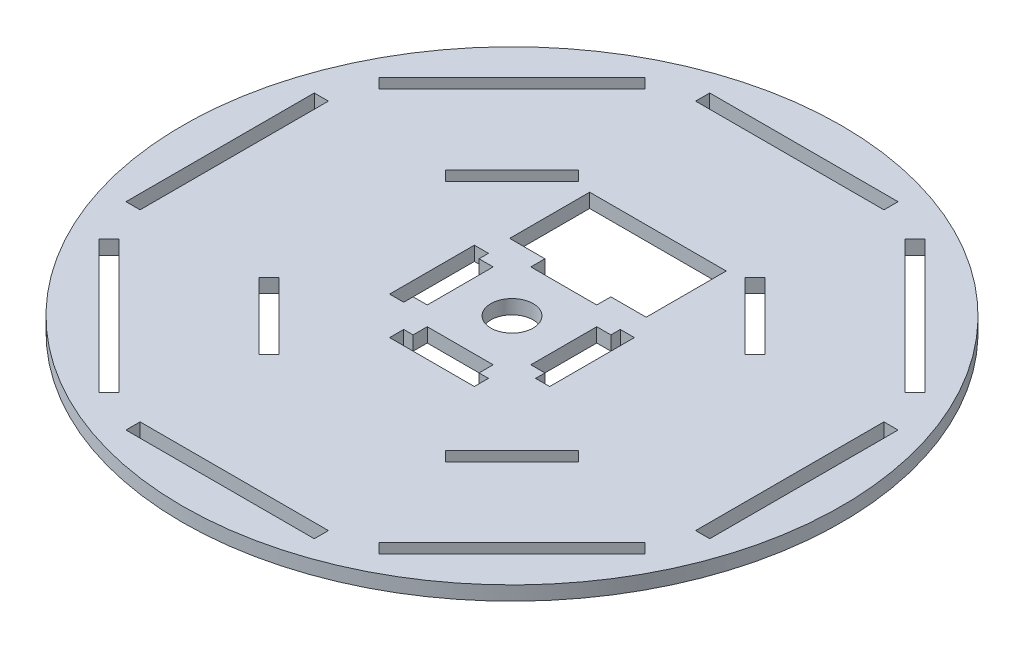
SolidWorks part; units mm, degrees
ref_plane "Alzado" through (0, 0, 0) normal (0, 0, 1) x (1, 0, 0)
ref_plane "Planta" through (0, 0, 0) normal (0, 1, 0) x (1, 0, 0)
ref_plane "Vista lateral" through (0, 0, 0) normal (1, 0, 0) x (0, 0, -1)
sketch "Croquis1" plane through (0, 0, 0) normal (0, 1, 0) x (1, 0, 0)
  line L0 (0, 11) -> (7, 11)
  line L1 (7, 11) -> (7, 14)
  line L2 (24.7487, 24.7487) -> (31.8198, 17.6777)
  line L3 (-7, 14) -> (-7, 11)
  line L4 (-7, 11) -> (0, 11)
  line L5 (11, 0) -> (11, 7)
  line L6 (11, 7) -> (14, 7)
  line L8 (14, -7) -> (11, -7)
  line L9 (11, -7) -> (11, 0)
  line L10 (0, 0) -> (-24.7487, 24.7487) construction
  line L11 (-24.7487, 24.7487) -> (-17.6777, 31.8198)
  line L12 (-17.6777, 31.8198) -> (-19.799, 33.9411)
  line L13 (-14, -7) -> (-11, -7)
  line L14 (-11, -7) -> (-11, 0)
  line L15 (-11, 0) -> (-11, 7)
  line L16 (-11, 7) -> (-14, 7)
  line L17 (-7, -14) -> (-9, -14)
  line L18 (7, -11) -> (7, -14)
  line L19 (0, -11) -> (7, -11)
  line L20 (14, -7) -> (14, -9)
  line L21 (-7, -14) -> (-7, -11)
  line L22 (-7, -11) -> (0, -11)
  line L23 (-19.799, 33.9411) -> (-33.9411, 19.799)
  line L24 (-24.7487, 24.7487) -> (-31.8198, 17.6777)
  line L25 (-31.8198, 17.6777) -> (-33.9411, 19.799)
  line L26 (7, 14) -> (14.5, 14)
  line L27 (14.5, 14) -> (14.5, 31)
  line L28 (14.5, 31) -> (-14.5, 31)
  line L29 (-14.5, 31) -> (-14.5, 14)
  line L30 (-14.5, 14) -> (-7, 14)
  line L31 (31.8198, 17.6777) -> (33.9411, 19.799)
  line L32 (33.9411, 19.799) -> (19.799, 33.9411)
  line L33 (17.6777, 31.8198) -> (19.799, 33.9411)
  line L34 (24.7487, 24.7487) -> (17.6777, 31.8198)
  line L35 (24.7487, -24.7487) -> (17.6777, -31.8198)
  line L36 (17.6777, -31.8198) -> (19.799, -33.9411)
  line L37 (19.799, -33.9411) -> (33.9411, -19.799)
  line L38 (31.8198, -17.6777) -> (33.9411, -19.799)
  line L39 (24.7487, -24.7487) -> (31.8198, -17.6777)
  line L40 (-24.7487, -24.7487) -> (-31.8198, -17.6777)
  line L41 (0, 0) -> (0, 62) construction
  line L42 (0, 62) -> (20, 62)
  line L43 (20, 62) -> (20, 59)
  line L44 (20, 59) -> (-20, 59)
  line L45 (-20, 59) -> (-20, 62)
  line L46 (-20, 62) -> (0, 62)
  line L47 (55.8614, 27.5772) -> (27.5772, 55.8614)
  line L48 (27.5772, 55.8614) -> (29.6985, 57.9828)
  line L49 (29.6985, 57.9828) -> (43.8406, 43.8406)
  line L50 (43.8406, 43.8406) -> (57.9828, 29.6985)
  line L51 (57.9828, 29.6985) -> (55.8614, 27.5772)
  line L52 (59, -20) -> (59, 20)
  line L53 (59, 20) -> (62, 20)
  line L54 (62, 20) -> (62, 0)
  line L55 (62, 0) -> (62, -20)
  line L56 (62, -20) -> (59, -20)
  line L57 (27.5772, -55.8614) -> (55.8614, -27.5772)
  line L58 (55.8614, -27.5772) -> (57.9828, -29.6985)
  line L59 (57.9828, -29.6985) -> (43.8406, -43.8406)
  line L60 (43.8406, -43.8406) -> (29.6985, -57.9828)
  line L61 (29.6985, -57.9828) -> (27.5772, -55.8614)
  line L62 (-20, -59) -> (20, -59)
  line L63 (20, -59) -> (20, -62)
  line L64 (20, -62) -> (0, -62)
  line L65 (0, -62) -> (-20, -62)
  line L66 (-20, -62) -> (-20, -59)
  line L67 (-55.8614, -27.5772) -> (-27.5772, -55.8614)
  line L68 (-27.5772, -55.8614) -> (-29.6985, -57.9828)
  line L69 (-29.6985, -57.9828) -> (-43.8406, -43.8406)
  line L70 (-43.8406, -43.8406) -> (-57.9828, -29.6985)
  line L71 (-57.9828, -29.6985) -> (-55.8614, -27.5772)
  line L72 (-59, 20) -> (-59, -20)
  line L73 (-59, -20) -> (-62, -20)
  line L74 (-62, -20) -> (-62, 0)
  line L75 (-62, 0) -> (-62, 20)
  line L76 (-62, 20) -> (-59, 20)
  line L77 (-27.5772, 55.8614) -> (-55.8614, 27.5772)
  line L78 (-55.8614, 27.5772) -> (-57.9828, 29.6985)
  line L79 (-57.9828, 29.6985) -> (-43.8406, 43.8406)
  line L80 (-43.8406, 43.8406) -> (-29.6985, 57.9828)
  line L81 (-29.6985, 57.9828) -> (-27.5772, 55.8614)
  line L82 (-31.8198, -17.6777) -> (-33.9411, -19.799)
  line L83 (-33.9411, -19.799) -> (-19.799, -33.9411)
  line L84 (-17.6777, -31.8198) -> (-19.799, -33.9411)
  line L85 (-24.7487, -24.7487) -> (-17.6777, -31.8198)
  line L86 (-14, 7) -> (-14, 9)
  line L87 (-14, 9) -> (-17, 9)
  line L88 (-17, 9) -> (-17, -9)
  line L89 (-17, -9) -> (-14, -9)
  line L90 (-14, -9) -> (-14, -7)
  line L92 (0, -17) -> (9, -17)
  line L93 (9, -17) -> (9, -14)
  line L94 (9, -14) -> (7, -14)
  line L95 (-9, -14) -> (-9, -17)
  line L96 (-9, -17) -> (0, -17)
  line L98 (17, 0) -> (17, 9)
  line L99 (17, 9) -> (14, 9)
  line L100 (14, 9) -> (14, 7)
  line L101 (14, -9) -> (17, -9)
  line L102 (17, -9) -> (17, 0)
  circle A0 centre (0, 0) radius 4.5
  circle A2 centre (0, 0) radius 70
  point P47 (0, 0)
  point P88 (0, 0)
  point P93 (0, 0)
  dimension "D1" = 9
  dimension "D2" = 14
  dimension "D3" = 140
  dimension "D4" = 7
  dimension "D5" = 3
  dimension "D6" = 14
  dimension "D7" = 35
  dimension "D8" = 3
  dimension "D9" = 10
  dimension "D10" = 3
  dimension "D11" = 20
  dimension "D12" = 10
  dimension "D14" = 62
  dimension "D15" = 20
  dimension "D16" = 3
  dimension "D17" = 40
  dimension "D19" = 17
  dimension "D13" = 4
  dimension "D20" = 29
  dimension "D21" = 3
  dimension "D23" = 3
  dimension "D24" = 18
  dimension "D26" = 9
  dimension "D27" = 18
  dimension "D29" = 9
  dimension "D18" = 8
extrude "Saliente-Extruir1" add sketch "Croquis1" along normal blind 3
